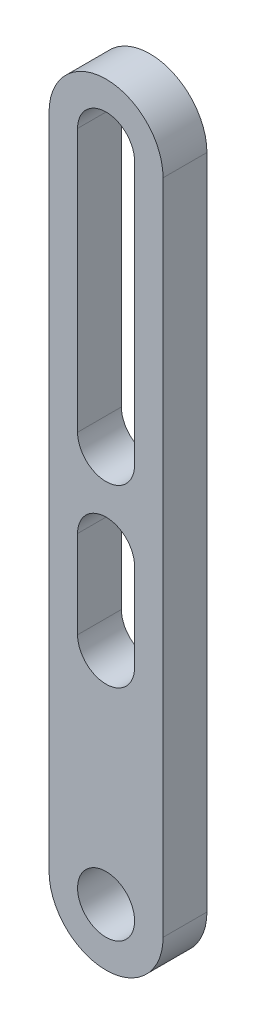
SolidWorks part; units mm, degrees
material "6061 Alloy"
ref_plane "Front Plane" through (0, 0, 0) normal (0, 0, 1) x (1, 0, 0)
ref_plane "Top Plane" through (0, 0, 0) normal (0, 1, 0) x (1, 0, 0)
ref_plane "Right Plane" through (0, 0, 0) normal (1, 0, 0) x (0, 0, -1)
sketch "Sketch1" plane through (0, 0, 0) normal (0, 0, 1) x (1, 0, 0)
  line L0 (0, -55) -> (0, 55) construction
  line L1 (-6.5, 75) -> (-6.5, 0)
  line L2 (55, 0) -> (-55, 0) construction
  line L3 (6.5, 75) -> (6.5, 0)
  line L4 (-3.25, 75) -> (-3.25, 45)
  line L5 (3.25, 45) -> (3.25, 75)
  line L6 (3.25, 35) -> (3.25, 25)
  line L7 (-3.25, 35) -> (-3.25, 25)
  line L8 (-3.25, 30) -> (16.4415, 30) construction
  line L9 (-3.25, 45) -> (18.8328, 45) construction
  circle A0 centre (0, 0) radius 3.25
  arc A1 (3.25, 75) -> (-3.25, 75) centre (0, 75) ccw
  arc A2 (-6.5, 0) -> (6.5, 0) centre (0, 0) ccw
  arc A3 (6.5, 75) -> (-6.5, 75) centre (0, 75) ccw
  arc A4 (-3.25, 45) -> (3.25, 45) centre (0, 45) ccw
  arc A5 (3.25, 35) -> (-3.25, 35) centre (0, 35) ccw
  arc A6 (-3.25, 25) -> (3.25, 25) centre (0, 25) ccw
  dimension "D1" = 6.5
  dimension "D2" = 75
  dimension "D3" = 6.5
  dimension "D4" = 3.25
  dimension "D5" = 30
  dimension "D6" = 45
  dimension "D7" = 10
extrude "Boss-Extrude1" add sketch "Sketch1" along normal blind 5
